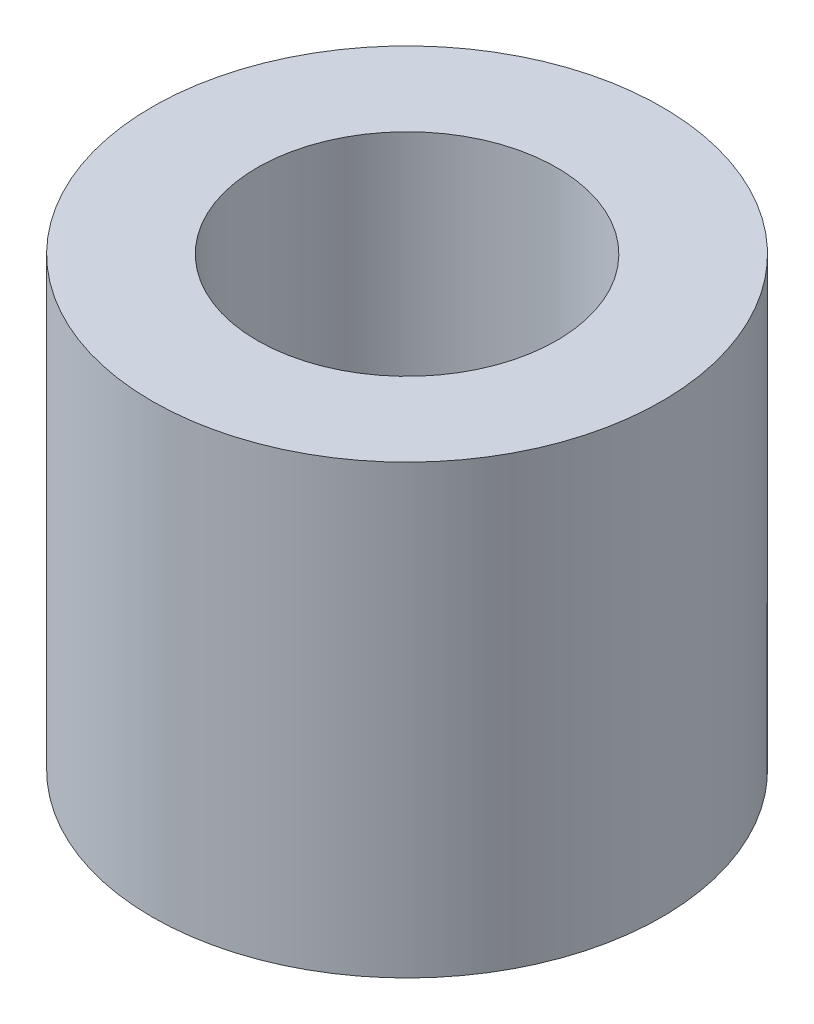
SolidWorks part; units mm, degrees
ref_plane "Front Plane" through (0, 0, 0) normal (0, 0, 1) x (1, 0, 0)
ref_plane "Top Plane" through (0, 0, 0) normal (0, 1, 0) x (1, 0, 0)
ref_plane "Right Plane" through (0, 0, 0) normal (1, 0, 0) x (0, 0, -1)
sketch "Sketch1" plane through (0, 0, 0) normal (0, 1, 0) x (1, 0, 0)
  circle A0 centre (0, 0) radius 1.425
  circle A1 centre (0, 0) radius 2.425
  dimension "D1" = 2.85
  dimension "D2" = 1
extrude "Boss-Extrude1" add sketch "Sketch1" along normal blind 4.25
